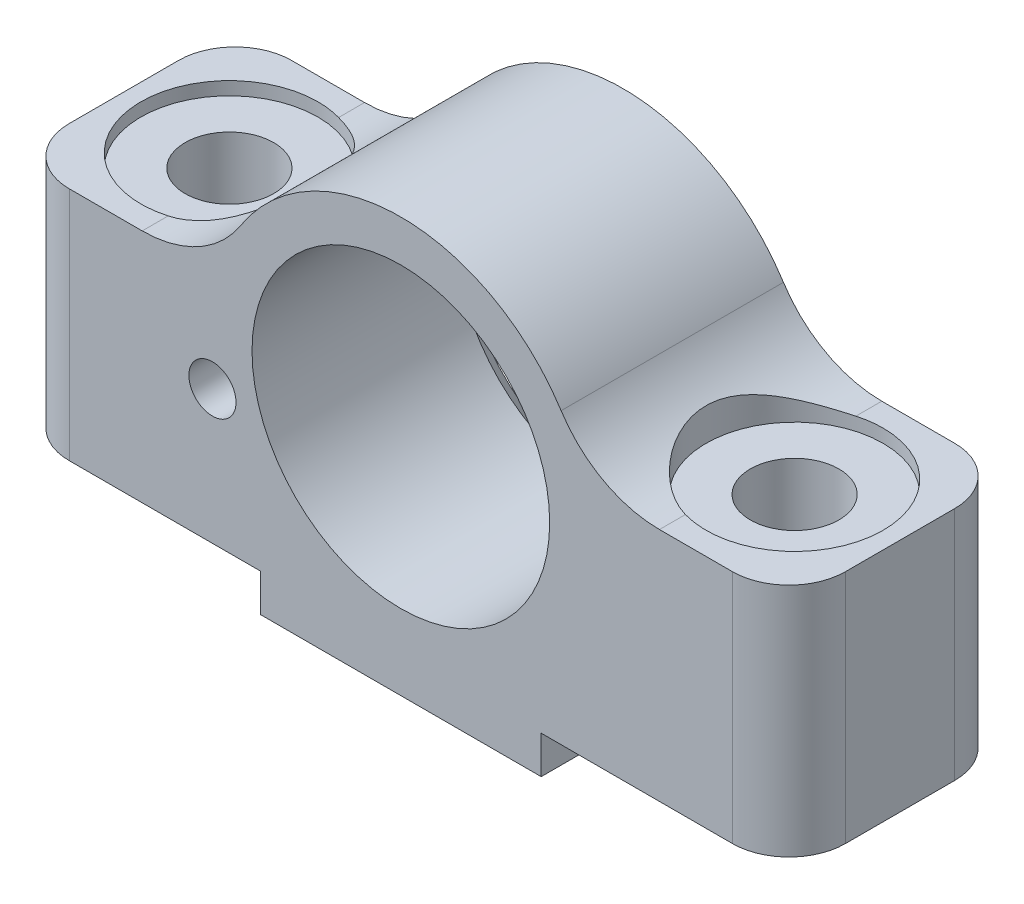
SolidWorks part; units mm, degrees
ref_plane "정면" through (0, 0, 0) normal (0, 0, 1) x (1, 0, 0)
ref_plane "윗면" through (0, 0, 0) normal (0, 1, 0) x (1, 0, 0)
ref_plane "우측면" through (0, 0, 0) normal (1, 0, 0) x (0, 0, -1)
sketch "스케치3" plane through (0, 0, 0) normal (0, 0, 1) x (1, 0, 0)
  line L0 (0, 0) -> (0, 17.9621) construction
  line L1 (-7.45, 0) -> (7.45, 0)
  line L2 (7.45, 0) -> (7.45, 2)
  line L3 (7.45, 2) -> (20.6, 2)
  line L4 (20.6, 2) -> (20.6, 14.5)
  line L5 (20.6, 14.5) -> (9.7658, 14.5)
  line L6 (-7.45, 0) -> (-7.45, 2)
  line L7 (-7.45, 2) -> (-20.6, 2)
  line L8 (-20.6, 2) -> (-20.6, 14.5)
  line L9 (-9.7658, 14.5) -> (-20.6, 14.5)
  circle A0 centre (0, 11.9) radius 7.9
  arc A1 (9.7658, 14.5) -> (-9.7658, 14.5) centre (0, 11.9) ccw
  point P12 (0, 14.7413)
  dimension "D4" = 9.9
  dimension "D5" = 15.8
  dimension "D1" = 14.9
  dimension "D2" = 41.2
  dimension "D3" = 12.5
  dimension "D6" = 2
extrude "보스-돌출1" add sketch "스케치3" along normal blind 11.8
fillet "필렛1" radius 6.2 2 edges at (-9.7658, 14.5, 5.9) (9.7658, 14.5, 5.9)
fillet "필렛2" radius 3 4 edges at (-20.6, 8.25, 11.8) (-20.6, 8.25, 0) (20.6, 8.25, 0) (20.6, 8.25, 11.8)
chamfer "모따기1" distance 1 angle 45 1 edges at (7.9, 11.9, 0)
hole_wizard "Ø4.7 (4.7) 지름 구멍2" positions "스케치7" profile "스케치8" hole size "Ø4.7" standard "ISO" end condition through all
sketch "스케치7" plane through (0, 0, 0) normal (0, 1, 0) x (1, 0, 0)
  line L0 (-13.7276, -11.8) -> (-17.6, -11.8) construction
  line L1 (-20.6, -8.8) -> (-20.6, -3) construction
  point P0 (15, -5.9)
  point P2 (-15, -5.9)
  point P13 (-16.542, -3.2862)
  dimension "D1" = 30
  dimension "D2" = 5.9
  dimension "D3" = 5.6
sketch "스케치8" plane through (15, 0, 5.9) normal (1, 0, 0) x (0, 0, -1)
  line L0 (0, 0) -> (0, 22.006)
  line L1 (0, 22.006) -> (2.35, 22.006)
  line L2 (2.35, 22.006) -> (2.35, 0)
  line L5 (2.35, 0) -> (0, 0)
  line L11 (0, -6.35) -> (0, 107.95) construction
  dimension "관통 구멍 지름" = 4.7
  dimension "관통 구멍 깊이" = 22.006
ref_plane "평면2" through (0, 13.8, 0) normal (0, 1, 0) x (1, 0, 0)
hole_wizard "Ø9.4 (9.4) 지름 구멍1" positions "스케치17" profile "스케치18" hole size "Ø9.4" standard "ISO"
sketch "스케치17" plane through (0, 13.8, 0) normal (0, 1, 0) x (1, 0, 0)
  point P0 (-15, -5.9)
  point P3 (15, -5.9)
sketch "스케치18" plane through (-15, 13.8, 5.9) normal (1, 0, 0) x (0, 0, -1)
  line L0 (0, 0) -> (0, 8.206)
  line L1 (0, 8.206) -> (4.7, 8.206)
  line L2 (4.7, 8.206) -> (4.7, 0)
  line L5 (4.7, 0) -> (0, 0)
  line L11 (0, -6.35) -> (0, 107.95) construction
  dimension "관통 구멍 지름" = 9.4
  dimension "관통 구멍 깊이" = 8.206
hole_wizard "M3 나사 구멍2" positions "스케치23" profile "스케치24" tap size "M3" standard "ISO"
sketch "스케치23" plane through (0, 0, 11.8) normal (0, 0, 1) x (1, 0, 0)
  line L0 (-17.6, 2) -> (-7.45, 2) construction
  point P0 (-10, 9.1)
  dimension "D1" = 10
  dimension "D2" = 7.1
sketch "스케치24" plane through (-10, 9.1, 11.8) normal (1, 0, 0) x (0, -1, 0)
  line L0 (0, 0) -> (0, 3.7511)
  line L1 (0, 3.7511) -> (1.25, 3)
  line L2 (1.25, 3) -> (1.25, 0)
  line L5 (1.25, 0) -> (0, 0)
  line L10 (0, 3.7511) -> (-1.25, 3) construction
  line L11 (0, -6.35) -> (0, 107.95) construction
  dimension "탭 드릴 지름" = 2.5
  dimension "탭 드릴 깊이" = 3
  dimension "드릴 각도" = 118
cosmetic thread "구멍 나사산1" parameters "D1"=0.5, "D2"=3
